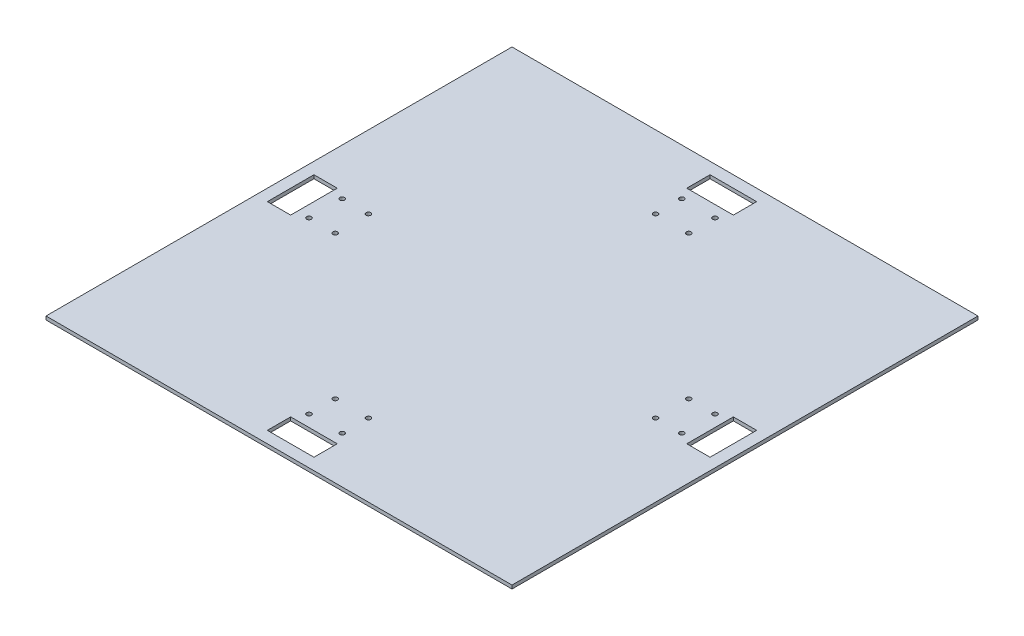
SolidWorks part; units mm, degrees
ref_plane "前视" through (0, 0, 0) normal (0, 0, 1) x (1, 0, 0)
ref_plane "上视" through (0, 0, 0) normal (0, 1, 0) x (1, 0, 0)
ref_plane "右视" through (0, 0, 0) normal (1, 0, 0) x (0, 0, -1)
sketch "Sketch1" plane through (0, 0, 0) normal (0, 1, 0) x (1, 0, 0)
  line L0 (200, 400) -> (200, -91.6949) construction
  line L1 (0, 0) -> (400, 0)
  line L2 (0, 0) -> (0, 400)
  line L3 (0, 400) -> (400, 400)
  line L4 (400, 0) -> (400, 400)
  line L5 (0, 200) -> (534.7225, 200) construction
  line L6 (10, 220) -> (10, 180)
  line L7 (180, 30) -> (220, 30)
  line L8 (180, 30) -> (180, 10)
  line L9 (180, 10) -> (220, 10)
  line L10 (220, 30) -> (220, 10)
  line L11 (30, 220) -> (10, 220)
  line L12 (30, 180) -> (10, 180)
  line L13 (30, 220) -> (30, 180)
  line L14 (220, 390) -> (180, 390)
  line L15 (220, 370) -> (220, 390)
  line L16 (180, 370) -> (180, 390)
  line L17 (220, 370) -> (180, 370)
  line L18 (390, 180) -> (390, 220)
  line L19 (370, 180) -> (390, 180)
  line L20 (370, 220) -> (390, 220)
  line L21 (370, 180) -> (370, 220)
  circle A0 centre (185.75, 40) radius 2
  circle A1 centre (185.75, 62.5) radius 2
  circle A2 centre (214.25, 62.5) radius 2
  circle A3 centre (214.25, 40) radius 2
  circle A4 centre (40, 214.25) radius 2
  circle A5 centre (62.5, 214.25) radius 2
  circle A6 centre (62.5, 185.75) radius 2
  circle A7 centre (40, 185.75) radius 2
  circle A8 centre (214.25, 360) radius 2
  circle A9 centre (214.25, 337.5) radius 2
  circle A10 centre (185.75, 337.5) radius 2
  circle A11 centre (185.75, 360) radius 2
  circle A12 centre (360, 185.75) radius 2
  circle A13 centre (337.5, 185.75) radius 2
  circle A14 centre (337.5, 214.25) radius 2
  circle A15 centre (360, 214.25) radius 2
  point P21 (200, 200)
  point P61 (200, 200)
  dimension "D7" = 10
  dimension "D8" = 14.25
  dimension "D11" = 4
  dimension "D1" = 400
  dimension "D2" = 400
  dimension "D3" = 20
  dimension "D4" = 40
  dimension "D5" = 20
  dimension "D6" = 10
  dimension "D9" = 32.5
  dimension "D10" = 4
extrude "Extrude1" add sketch "Sketch1" along normal blind 3
